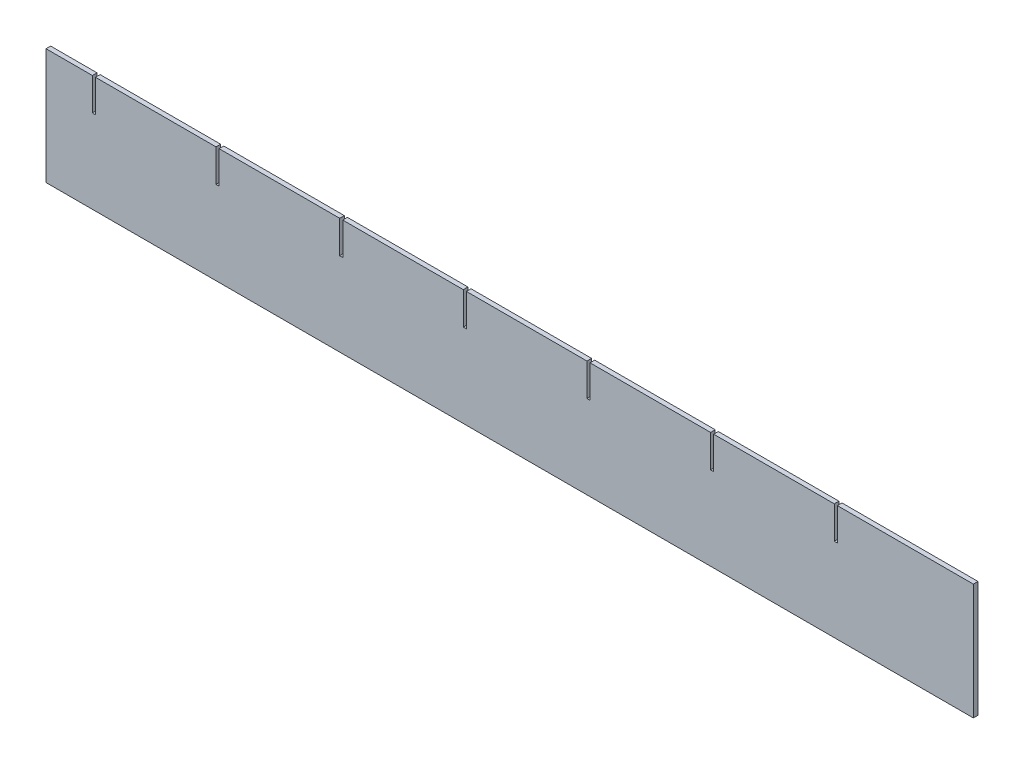
SolidWorks part; units mm, degrees
ref_plane "Front Plane" through (0, 0, 0) normal (0, 0, 1) x (1, 0, 0)
ref_plane "Top Plane" through (0, 0, 0) normal (0, 1, 0) x (1, 0, 0)
ref_plane "Right Plane" through (0, 0, 0) normal (1, 0, 0) x (0, 0, -1)
sketch "Sketch1" plane through (0, 0, 0) normal (0, 0, 1) x (1, 0, 0)
  line L0 (-268, 37.5) -> (300, 37.5)
  line L1 (-300, 37.5) -> (-270, 37.5)
  line L2 (-300, 37.5) -> (-300, -37.5)
  line L3 (-300, -37.5) -> (300, -37.5)
  line L4 (300, 37.5) -> (300, -37.5)
  line L5 (-300, 37.5) -> (300, -37.5) construction
  line L6 (-300, -37.5) -> (300, 37.5) construction
  line L8 (-270, 37.5) -> (-270, 16.5)
  line L9 (-270, 16.5) -> (-268, 16.5)
  line L10 (-268, 37.5) -> (-268, 16.5)
  line L11 (-188, 37.5) -> (-188, 16.5)
  line L12 (-190, 37.5) -> (-190, 16.5)
  line L13 (-190, 16.5) -> (-188, 16.5)
  line L14 (-108, 37.5) -> (-108, 16.5)
  line L15 (-110, 37.5) -> (-110, 16.5)
  line L16 (-110, 16.5) -> (-108, 16.5)
  line L17 (-28, 37.5) -> (-28, 16.5)
  line L18 (-30, 37.5) -> (-30, 16.5)
  line L19 (-30, 16.5) -> (-28, 16.5)
  line L20 (52, 37.5) -> (52, 16.5)
  line L21 (50, 37.5) -> (50, 16.5)
  line L22 (50, 16.5) -> (52, 16.5)
  line L23 (132, 37.5) -> (132, 16.5)
  line L24 (130, 37.5) -> (130, 16.5)
  line L25 (130, 16.5) -> (132, 16.5)
  line L26 (212, 37.5) -> (212, 16.5)
  line L27 (210, 37.5) -> (210, 16.5)
  line L28 (210, 16.5) -> (212, 16.5)
  line L29 (-268, 37.5) -> (-188, 37.5) construction
  point P0 (0, 0)
  dimension "D1" = 75
  dimension "D2" = 600
  dimension "D3" = 2
  dimension "D4" = 21
  dimension "D5" = 30
  dimension "D7" = 80
  dimension "D6" = 7
extrude "Boss-Extrude1" add sketch "Sketch1" along normal blind 3 contours L28 L27 L0 L23 L25 L24 L20 L22 L21 L17 L19 L18 L14 L16 L15 L11 L13 L12 L10 L9 L8 L1 L2 L3 L4 L26
